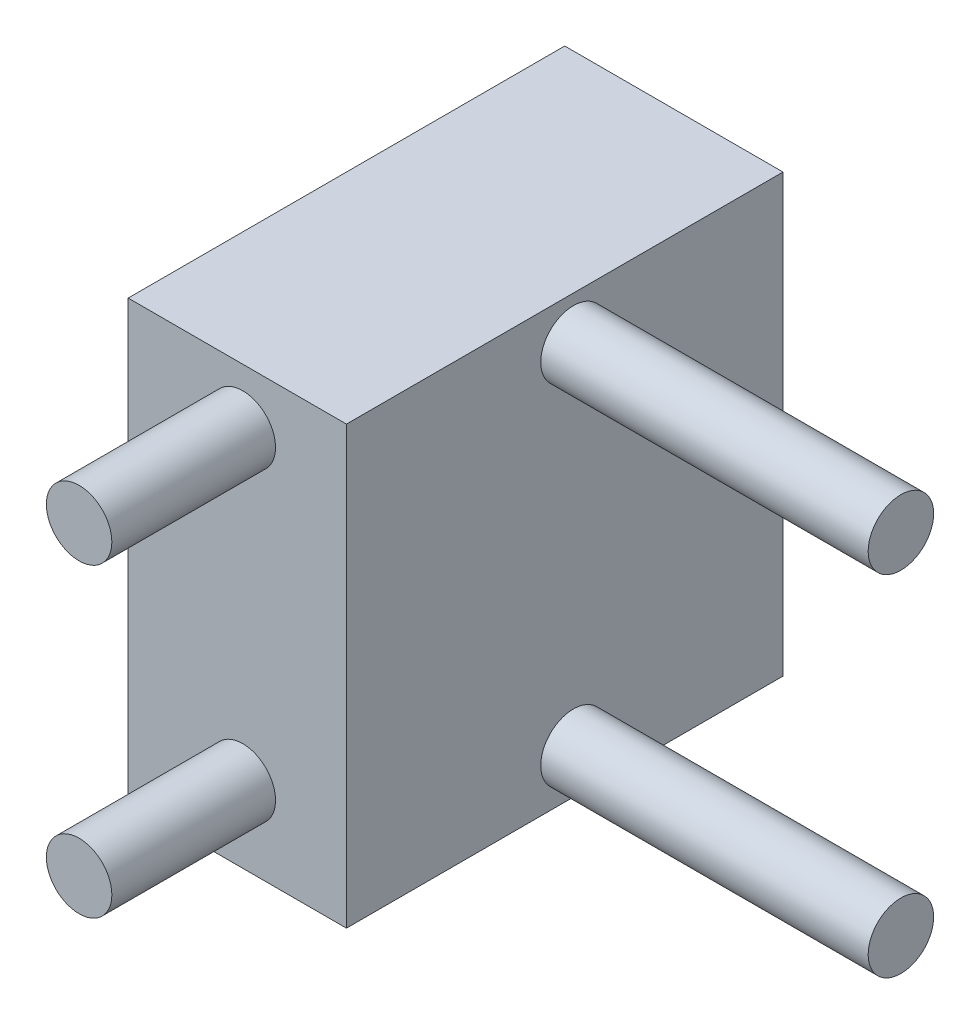
SolidWorks part; units mm, degrees
material "1023 Carbon Steel Sheet (SS)"
ref_plane "Front Plane" through (0, 0, 0) normal (0, 0, 1) x (1, 0, 0)
ref_plane "Top Plane" through (0, 0, 0) normal (0, 1, 0) x (1, 0, 0)
ref_plane "Right Plane" through (0, 0, 0) normal (1, 0, 0) x (0, 0, -1)
sketch "Sketch2" plane through (0, 0, 0) normal (0, 1, 0) x (1, 0, 0)
  line L0 (0, 0) -> (0, 20)
  line L1 (0, 20) -> (10, 20)
  line L2 (10, 20) -> (10, 0)
  line L3 (10, 0) -> (0, 0)
  dimension "D1" = 10
  dimension "D2" = 20
extrude "Boss-Extrude1" add sketch "Sketch2" along normal blind 20
sketch "Sketch3" plane through (0, 0, 0) normal (0, 0, 1) x (1, 0, 0)
  circle A0 centre (5.252, 3.4472) radius 1.5
  circle A1 centre (5.252, 17.4472) radius 1.5
  dimension "D2" = 3
  dimension "D3" = 3
  dimension "D1" = 14
extrude "Boss-Extrude2" add sketch "Sketch3" along normal blind 7.5
sketch "Sketch4" plane through (10, 0, 0) normal (1, 0, 0) x (0, 0, -1)
  circle A0 centre (10.1775, 9.9107) radius 0.75
  dimension "D1" = 1.5
sketch "Sketch5" plane through (10, 0, 0) normal (1, 0, 0) x (0, 0, -1)
  circle A0 centre (10.1775, 9.9107) radius 1.5
  dimension "D1" = 3
sketch "Sketch6" plane through (10, 0, 0) normal (1, 0, 0) x (0, 0, -1)
  line L0 (0, 0) -> (20, 0) construction
  circle A0 centre (10.4006, 2) radius 1.5
  dimension "D1" = 3
  dimension "D2" = 3
  dimension "D3" = 2
extrude "Boss-Extrude4" add sketch "Sketch6" along normal blind 15
sketch "Sketch8" plane through (10, 0, 0) normal (1, 0, 0) x (0, 0, -1)
  line L0 (0, 20) -> (20, 20) construction
  circle A0 centre (10.4006, 18) radius 1.5
  point P5 (0, 0)
  dimension "D1" = 3
  dimension "D2" = 2
extrude "Boss-Extrude5" add sketch "Sketch8" along normal blind 15
